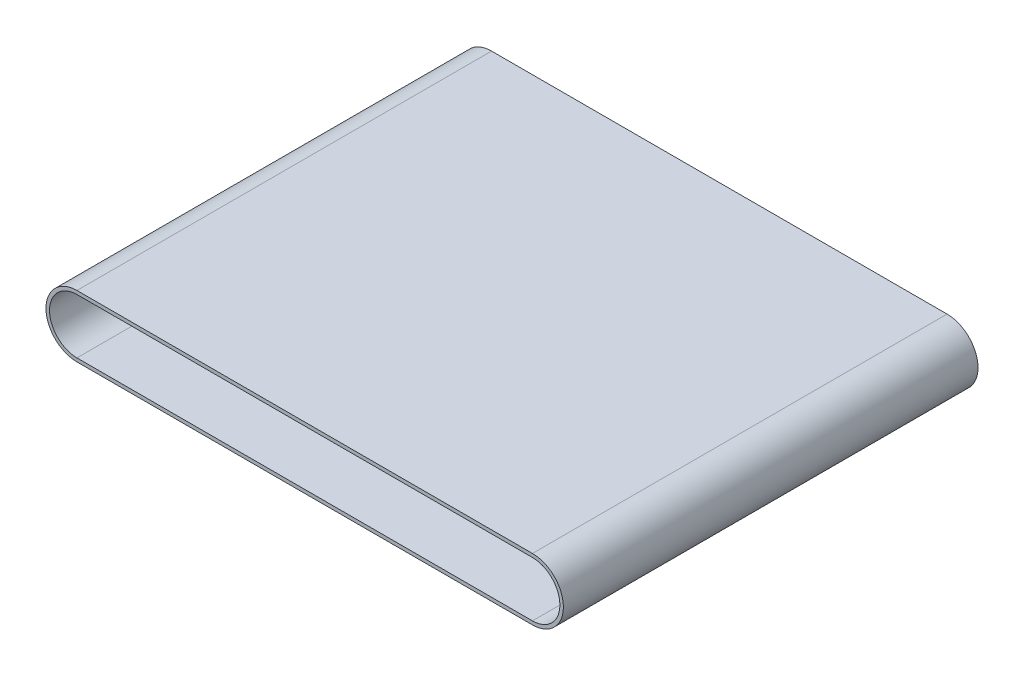
SolidWorks part; units mm, degrees
ref_plane "Front Plane" through (0, 0, 0) normal (0, 0, 1) x (1, 0, 0)
ref_plane "Top Plane" through (0, 0, 0) normal (0, 1, 0) x (1, 0, 0)
ref_plane "Right Plane" through (0, 0, 0) normal (1, 0, 0) x (0, 0, -1)
ref_plane "Plane1" through (0, 0, 177.5) normal (0, 0, 1) x (1, 0, 0)
sketch "Sketch1" plane through (0, 0, 177.5) normal (0, 0, 1) x (1, 0, 0)
  line L0 (0, -23.5) -> (-390, -23.5)
  line L1 (-390, 23.5) -> (0, 23.5)
  line L2 (-390, -26.5) -> (0, -26.5)
  line L3 (0, 26.5) -> (-390, 26.5)
  arc A0 (-390, -23.5) -> (-390, 23.5) centre (-390, 0) cw
  arc A1 (0, 23.5) -> (0, -23.5) centre (0, 0) cw
  arc A2 (-390, 26.5) -> (-390, -26.5) centre (-390, 0) ccw
  arc A3 (0, -26.5) -> (0, 26.5) centre (0, 0) ccw
extrude "Boss-Extrude1" add sketch "Sketch1" against normal blind 355
